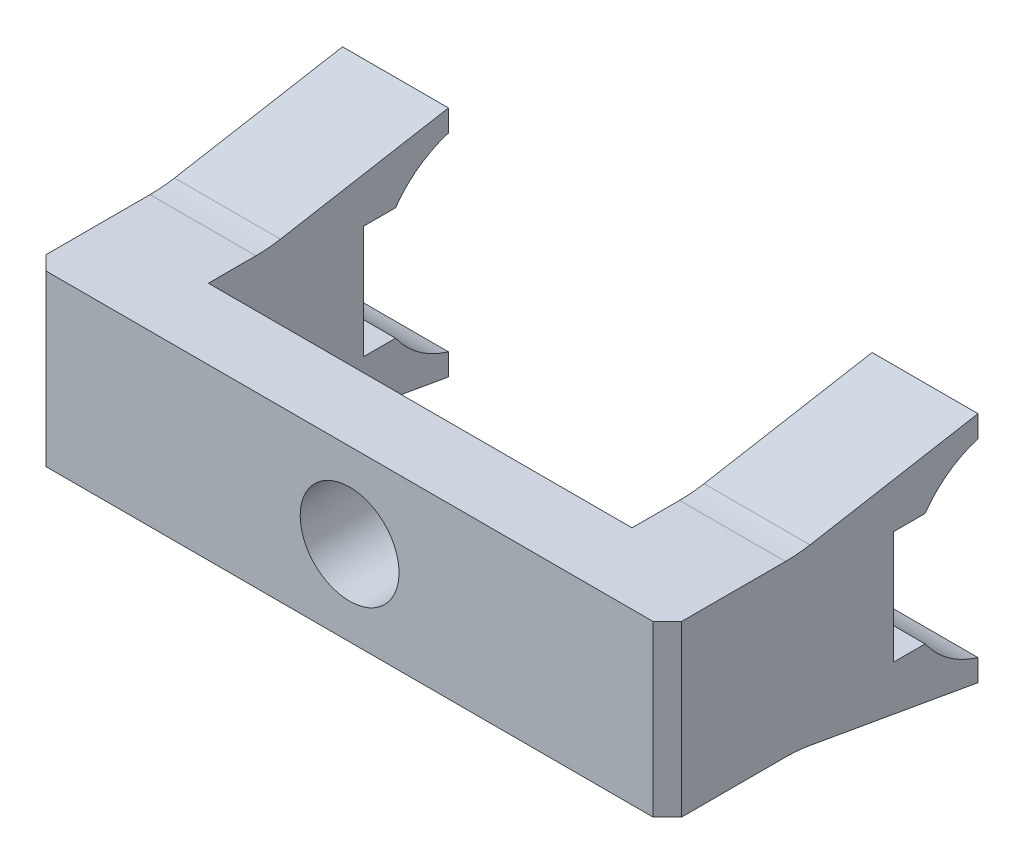
SolidWorks part; units mm, degrees
ref_plane "前视基准面" through (0, 0, 0) normal (0, 0, 1) x (1, 0, 0)
ref_plane "上视基准面" through (0, 0, 0) normal (0, 1, 0) x (1, 0, 0)
ref_plane "右视基准面" through (0, 0, 0) normal (1, 0, 0) x (0, 0, -1)
sketch "草图1" plane through (0, 0, 0) normal (0, 0, 1) x (1, 0, 0)
  line L1 (-22.5, -6) -> (22.5, -6)
  line L2 (-22.5, -6) -> (-22.5, 6)
  line L3 (-22.5, 6) -> (22.5, 6)
  line L4 (22.5, -6) -> (22.5, 6)
  line L5 (-22.5, -6) -> (22.5, 6) construction
  line L6 (-22.5, 6) -> (22.5, -6) construction
  point P0 (0, 0)
  dimension "D1" = 45
  dimension "D2" = 12
extrude "凸台-拉伸1" add sketch "草图1" along normal blind 5
sketch "草图4" plane through (22.5, 0, 0) normal (1, 0, 0) x (0, 0, -1)
  line L0 (0, 6) -> (3.3647, 6)
  line L2 (26.5445, 0) -> (-13.0765, 0) construction
  line L4 (11, 4) -> (11, -4)
  line L5 (17, 8.25) -> (17, 6.7082)
  line L6 (0, -6) -> (3.3647, -6)
  line L7 (11, 4) -> (13.2554, 4)
  line L8 (11, -4) -> (13.2554, -4)
  line L9 (17, -6.7082) -> (17, -8.25)
  line L10 (0, 6) -> (0, -6)
  line L11 (-5, -6) -> (-5, 6) construction
  line L12 (17, 8.25) -> (5.1012, 6.1519)
  line L13 (17, -8.25) -> (5.1012, -6.1519)
  arc A6 (17, 6.7082) -> (13.2554, 4) centre (19, 0) ccw
  arc A7 (13.2554, -4) -> (17, -6.7082) centre (19, 0) ccw
  arc A8 (3.3647, 6) -> (5.1012, 6.1519) centre (3.3647, 16) ccw
  arc A10 (3.3647, -6) -> (5.1012, -6.1519) centre (3.3647, -16) cw
  point P2 (7.1676, 16)
  point P3 (5.1315, 16)
  point P10 (0, 0)
  point P29 (11, 0)
  dimension "D1" = 16.5
  dimension "D3" = 22
  dimension "D4" = 24
  dimension "D5" = 16
  dimension "D7" = 7
  dimension "D8" = 7
  dimension "D9" = 20
  dimension "D2" = 10
  dimension "D6" = 8
extrude "凸台-拉伸2" add sketch "草图4" against normal blind 7.5
mirror "镜向1" about plane through (0, 0, 0) normal (1, 0, 0) of "凸台-拉伸2"
sketch "草图9" plane through (0, 0, 0) normal (0, 0, -1) x (-1, 0, 0)
  circle A0 centre (0, 0) radius 3.5
extrude "切除-拉伸1" cut sketch "草图9" against normal through all
hole_wizard "M6 螺纹孔1" positions "草图10" profile "草图12" tap size "M6" standard "GB"
sketch "草图10" plane through (0, 0, -11) normal (0, 0, -1) x (-1, 0, 0)
  point P0 (-19, 0)
  dimension "D1" = 19
sketch "草图12" plane through (19, 0, -11) normal (1, 0, 0) x (0, 1, 0)
  line L0 (0, 0) -> (0, 13.5022)
  line L1 (0, 13.5022) -> (2.5, 12)
  line L2 (2.5, 12) -> (2.5, 0)
  line L5 (2.5, 0) -> (0, 0)
  line L10 (0, 13.5022) -> (-2.5, 12) construction
  line L11 (0, -6.35) -> (0, 107.95) construction
  dimension "螺纹孔钻头直径" = 5
  dimension "螺纹孔钻头深度" = 12
  dimension "导头角度" = 118
cosmetic thread "孔螺蚊线1" parameters "D1"=9, "D2"=6
mirror "镜向2" about plane through (0, 0, 0) normal (1, 0, 0) of "M6 螺纹孔1"
chamfer "倒角1" distance 1 angle 45 2 edges at (-22.5, 0, 5) (22.5, 0, 5)
